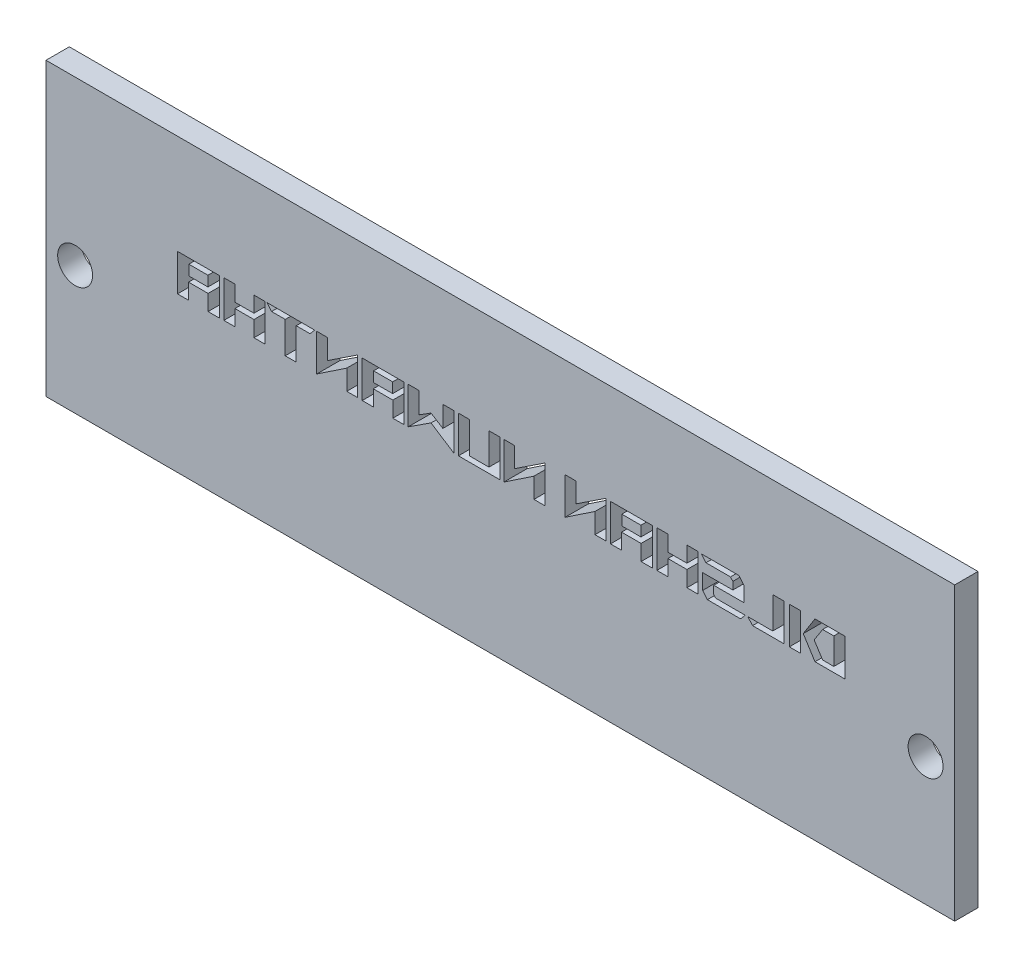
SolidWorks part; units mm, degrees
ref_plane "Front Plane" through (0, 0, 0) normal (0, 0, 1) x (1, 0, 0)
ref_plane "Top Plane" through (0, 0, 0) normal (0, 1, 0) x (1, 0, 0)
ref_plane "Right Plane" through (0, 0, 0) normal (1, 0, 0) x (0, 0, -1)
sketch "Sketch1" plane through (0, 0, 0) normal (0, 0, 1) x (1, 0, 0)
  line L1 (-39, 12.5) -> (39, 12.5)
  line L2 (-39, 12.5) -> (-39, -12.5)
  line L3 (-39, -12.5) -> (39, -12.5)
  line L4 (39, 12.5) -> (39, -12.5)
  line L5 (-39, 12.5) -> (39, -12.5) construction
  line L6 (-39, -12.5) -> (39, 12.5) construction
  point P0 (0, 0)
  dimension "D1" = 25
  dimension "D2" = 78
extrude "Boss-Extrude1" add sketch "Sketch1" along normal blind 2 contours L1 L4 L3 L2
sketch "Sketch2" plane through (0, 0, 2) normal (0, 0, 1) x (1, 0, 0)
  line L0 (-39, 12.5) -> (39, 12.5) construction
  line L1 (-39, 12.5) -> (-39, -12.5) construction
  circle A0 centre (-36.5, -1.5) radius 1.5
  circle A1 centre (36.5, -1.5) radius 1.5
  dimension "D1" = 14
  dimension "D2" = 14
  dimension "D3" = 73
  dimension "D4" = 2.5
extrude "Cut-Extrude1" cut sketch "Sketch2" against normal blind 2
sketch "Sketch3" plane through (0, 0, 0) normal (0, 0, -1) x (-1, 0, 0)
  text T0 "Dilshan Nuwantha" font "ROG Fonts" height 3.175
extrude "Cut-Extrude2" cut sketch "Sketch3" against normal blind 2
